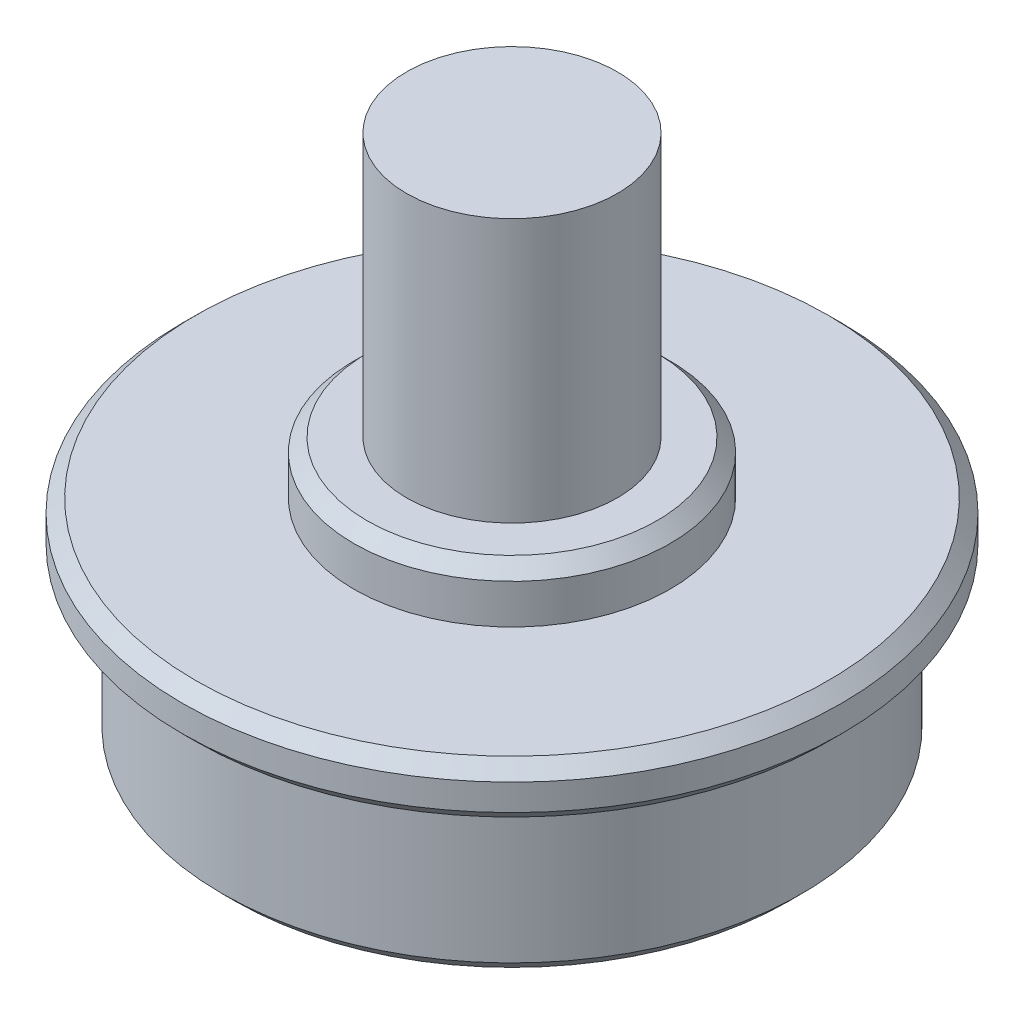
SolidWorks part; units mm, degrees
material "AISI 304"
ref_plane "Front Plane" through (0, 0, 0) normal (0, 0, 1) x (1, 0, 0)
ref_plane "Top Plane" through (0, 0, 0) normal (0, 1, 0) x (1, 0, 0)
ref_plane "Right Plane" through (0, 0, 0) normal (1, 0, 0) x (0, 0, -1)
sketch "Sketch1" plane through (0, 0, 0) normal (0, 1, 0) x (1, 0, 0)
  circle A0 centre (0, 0) radius 6.25
  dimension "D1" = 12.5
extrude "Boss-Extrude1" add sketch "Sketch1" along normal blind 1
sketch "Sketch2" plane through (0, 0, 0) normal (0, -1, 0) x (1, 0, 0)
  circle A0 centre (0, 0) radius 5.5
  dimension "D1" = 11
extrude "Boss-Extrude2" add sketch "Sketch2" along normal blind 3
sketch "Sketch3" plane through (0, 1, 0) normal (0, 1, 0) x (1, 0, 0)
  circle A0 centre (0, 0) radius 3
  dimension "D1" = 6
extrude "Boss-Extrude3" add sketch "Sketch3" along normal blind 1
sketch "Sketch4" plane through (0, 2, 0) normal (0, 1, 0) x (1, 0, 0)
  circle A0 centre (0, 0) radius 2
  dimension "D1" = 4
extrude "Boss-Extrude4" add sketch "Sketch4" along normal blind 5
cosmetic thread "Cosmetic Thread1" parameters "D1"=4, "D2"=3.242
chamfer "Chamfer1" distance 0.25 angle 45 3 edges at (0, 0, 6.25) (0, -3, -5.5) (0, 1, 6.25)
chamfer "Chamfer2" distance 0.25 angle 45 1 edges at (0, 2, 3)
